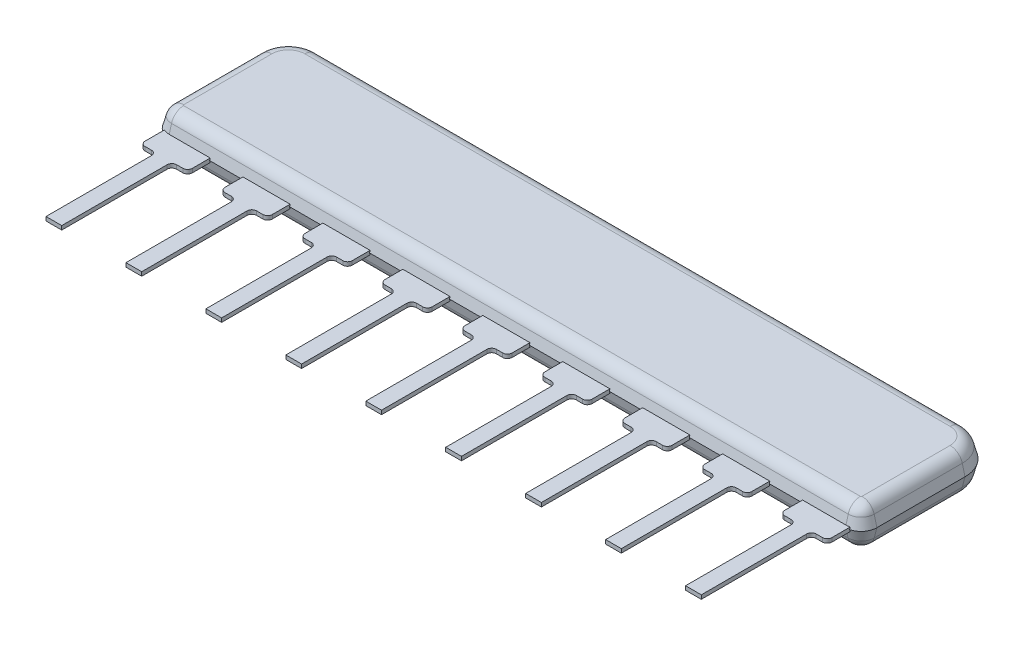
SolidWorks part; units mm, degrees
ref_plane "Front" through (0, 0, 0) normal (0, 0, 1) x (1, 0, 0)
ref_plane "Top" through (0, 0, 0) normal (0, 1, 0) x (1, 0, 0)
ref_plane "Right" through (0, 0, 0) normal (1, 0, 0) x (0, 0, -1)
sketch "Sketch1" plane through (0, 0, 0) normal (0, 1, 0) x (1, 0, 0)
  line L1 (0.5, 0) -> (22, 0)
  line L2 (0, 0.5) -> (0, 3.3)
  line L3 (1, 4.3) -> (21.5, 4.3)
  line L4 (22.5, 0.5) -> (22.5, 3.3)
  arc A0 (0, 3.3) -> (1, 4.3) centre (1, 3.3) cw
  arc A2 (22.5, 3.3) -> (21.5, 4.3) centre (21.5, 3.3) ccw
  arc A4 (0.5, 0) -> (0, 0.5) centre (0.5, 0.5) cw
  arc A5 (22, 0) -> (22.5, 0.5) centre (22, 0.5) ccw
  point P7 (0, 4.3)
  point P10 (0, 0)
  point P13 (22.5, 4.3)
  point P16 (22.5, 0)
  dimension "D3" = 1
  dimension "D4" = 0.5
  dimension "D1" = 22.5
  dimension "D2" = 4.3
extrude "Extrude1" add sketch "Sketch1" along normal mid plane 1.25 draft 15
sketch "Sketch2" plane through (0, 0, 0) normal (0, 1, 0) x (1, 0, 0)
  line L0 (0.3, 0.4022) -> (0.3, -0.55)
  line L2 (0.45, -0.7) -> (0.65, -0.7)
  line L3 (0.8, -0.85) -> (0.8, -4.2)
  line L4 (0.8, -4.2) -> (1.3, -4.2)
  line L5 (1.3, -4.2) -> (1.3, -0.85)
  line L6 (1.45, -0.7) -> (1.65, -0.7)
  line L7 (1.8, -0.55) -> (1.8, 0.4022)
  line L8 (0.3, 0.4022) -> (1.8, 0.4022)
  line L9 (2.84, 0.4022) -> (2.84, -0.55)
  line L10 (2.99, -0.7) -> (3.19, -0.7)
  line L11 (3.34, -0.85) -> (3.34, -4.2)
  line L12 (3.34, -4.2) -> (3.84, -4.2)
  line L13 (3.84, -4.2) -> (3.84, -0.85)
  line L14 (3.99, -0.7) -> (4.19, -0.7)
  line L15 (4.34, -0.55) -> (4.34, 0.4022)
  line L16 (2.84, 0.4022) -> (4.34, 0.4022)
  line L17 (5.38, 0.4022) -> (5.38, -0.55)
  line L18 (5.53, -0.7) -> (5.73, -0.7)
  line L19 (5.88, -0.85) -> (5.88, -4.2)
  line L20 (5.88, -4.2) -> (6.38, -4.2)
  line L21 (6.38, -4.2) -> (6.38, -0.85)
  line L22 (6.53, -0.7) -> (6.73, -0.7)
  line L23 (6.88, -0.55) -> (6.88, 0.4022)
  line L24 (5.38, 0.4022) -> (6.88, 0.4022)
  line L25 (7.92, 0.4022) -> (7.92, -0.55)
  line L26 (8.07, -0.7) -> (8.27, -0.7)
  line L27 (8.42, -0.85) -> (8.42, -4.2)
  line L28 (8.42, -4.2) -> (8.92, -4.2)
  line L29 (8.92, -4.2) -> (8.92, -0.85)
  line L30 (9.07, -0.7) -> (9.27, -0.7)
  line L31 (9.42, -0.55) -> (9.42, 0.4022)
  line L32 (7.92, 0.4022) -> (9.42, 0.4022)
  line L33 (10.46, 0.4022) -> (10.46, -0.55)
  line L34 (10.61, -0.7) -> (10.81, -0.7)
  line L35 (10.96, -0.85) -> (10.96, -4.2)
  line L36 (10.96, -4.2) -> (11.46, -4.2)
  line L37 (11.46, -4.2) -> (11.46, -0.85)
  line L38 (11.61, -0.7) -> (11.81, -0.7)
  line L39 (11.96, -0.55) -> (11.96, 0.4022)
  line L40 (10.46, 0.4022) -> (11.96, 0.4022)
  line L41 (13, 0.4022) -> (13, -0.55)
  line L42 (13.15, -0.7) -> (13.35, -0.7)
  line L43 (13.5, -0.85) -> (13.5, -4.2)
  line L44 (13.5, -4.2) -> (14, -4.2)
  line L45 (14, -4.2) -> (14, -0.85)
  line L46 (14.15, -0.7) -> (14.35, -0.7)
  line L47 (14.5, -0.55) -> (14.5, 0.4022)
  line L48 (13, 0.4022) -> (14.5, 0.4022)
  line L49 (15.54, 0.4022) -> (15.54, -0.55)
  line L50 (15.69, -0.7) -> (15.89, -0.7)
  line L51 (16.04, -0.85) -> (16.04, -4.2)
  line L52 (16.04, -4.2) -> (16.54, -4.2)
  line L53 (16.54, -4.2) -> (16.54, -0.85)
  line L54 (16.69, -0.7) -> (16.89, -0.7)
  line L55 (17.04, -0.55) -> (17.04, 0.4022)
  line L56 (15.54, 0.4022) -> (17.04, 0.4022)
  line L57 (18.08, 0.4022) -> (18.08, -0.55)
  line L58 (18.23, -0.7) -> (18.43, -0.7)
  line L59 (18.58, -0.85) -> (18.58, -4.2)
  line L60 (18.58, -4.2) -> (19.08, -4.2)
  line L61 (19.08, -4.2) -> (19.08, -0.85)
  line L62 (19.23, -0.7) -> (19.43, -0.7)
  line L63 (19.58, -0.55) -> (19.58, 0.4022)
  line L64 (18.08, 0.4022) -> (19.58, 0.4022)
  line L65 (20.62, 0.4022) -> (20.62, -0.55)
  line L66 (20.77, -0.7) -> (20.97, -0.7)
  line L67 (21.12, -0.85) -> (21.12, -4.2)
  line L68 (21.12, -4.2) -> (21.62, -4.2)
  line L69 (21.62, -4.2) -> (21.62, -0.85)
  line L70 (21.77, -0.7) -> (21.97, -0.7)
  line L71 (22.12, -0.55) -> (22.12, 0.4022)
  line L72 (20.62, 0.4022) -> (22.12, 0.4022)
  line L73 (0, 3.3) -> (0, 0.5) construction
  line L75 (0.5, 0) -> (22, 0) construction
  arc A0 (0.3, -0.55) -> (0.45, -0.7) centre (0.45, -0.55) ccw
  arc A1 (1.8, -0.55) -> (1.65, -0.7) centre (1.65, -0.55) cw
  arc A2 (1.3, -0.85) -> (1.45, -0.7) centre (1.45, -0.85) cw
  arc A3 (0.65, -0.7) -> (0.8, -0.85) centre (0.65, -0.85) cw
  arc A4 (2.84, -0.55) -> (2.99, -0.7) centre (2.99, -0.55) ccw
  arc A5 (4.34, -0.55) -> (4.19, -0.7) centre (4.19, -0.55) cw
  arc A6 (3.84, -0.85) -> (3.99, -0.7) centre (3.99, -0.85) cw
  arc A7 (3.19, -0.7) -> (3.34, -0.85) centre (3.19, -0.85) cw
  arc A8 (5.38, -0.55) -> (5.53, -0.7) centre (5.53, -0.55) ccw
  arc A9 (6.88, -0.55) -> (6.73, -0.7) centre (6.73, -0.55) cw
  arc A10 (6.38, -0.85) -> (6.53, -0.7) centre (6.53, -0.85) cw
  arc A11 (5.73, -0.7) -> (5.88, -0.85) centre (5.73, -0.85) cw
  arc A12 (7.92, -0.55) -> (8.07, -0.7) centre (8.07, -0.55) ccw
  arc A13 (9.42, -0.55) -> (9.27, -0.7) centre (9.27, -0.55) cw
  arc A14 (8.92, -0.85) -> (9.07, -0.7) centre (9.07, -0.85) cw
  arc A15 (8.27, -0.7) -> (8.42, -0.85) centre (8.27, -0.85) cw
  arc A16 (10.46, -0.55) -> (10.61, -0.7) centre (10.61, -0.55) ccw
  arc A17 (11.96, -0.55) -> (11.81, -0.7) centre (11.81, -0.55) cw
  arc A18 (11.46, -0.85) -> (11.61, -0.7) centre (11.61, -0.85) cw
  arc A19 (10.81, -0.7) -> (10.96, -0.85) centre (10.81, -0.85) cw
  arc A20 (13, -0.55) -> (13.15, -0.7) centre (13.15, -0.55) ccw
  arc A21 (14.5, -0.55) -> (14.35, -0.7) centre (14.35, -0.55) cw
  arc A22 (14, -0.85) -> (14.15, -0.7) centre (14.15, -0.85) cw
  arc A23 (13.35, -0.7) -> (13.5, -0.85) centre (13.35, -0.85) cw
  arc A24 (15.54, -0.55) -> (15.69, -0.7) centre (15.69, -0.55) ccw
  arc A25 (17.04, -0.55) -> (16.89, -0.7) centre (16.89, -0.55) cw
  arc A26 (16.54, -0.85) -> (16.69, -0.7) centre (16.69, -0.85) cw
  arc A27 (15.89, -0.7) -> (16.04, -0.85) centre (15.89, -0.85) cw
  arc A28 (18.08, -0.55) -> (18.23, -0.7) centre (18.23, -0.55) ccw
  arc A29 (19.58, -0.55) -> (19.43, -0.7) centre (19.43, -0.55) cw
  arc A30 (19.08, -0.85) -> (19.23, -0.7) centre (19.23, -0.85) cw
  arc A31 (18.43, -0.7) -> (18.58, -0.85) centre (18.43, -0.85) cw
  arc A32 (20.62, -0.55) -> (20.77, -0.7) centre (20.77, -0.55) ccw
  arc A33 (22.12, -0.55) -> (21.97, -0.7) centre (21.97, -0.55) cw
  arc A34 (21.62, -0.85) -> (21.77, -0.7) centre (21.77, -0.85) cw
  arc A35 (20.97, -0.7) -> (21.12, -0.85) centre (20.97, -0.85) cw
  point P12 (0.3, -0.7)
  dimension "D5" = 0.15
  dimension "D1" = 0.7
  dimension "D2" = 1.5
  dimension "D3" = 0.5
  dimension "D4" = 0.5
  dimension "D6" = 0.3
  dimension "D7" = 3.5
extrude "Extrude2" add sketch "Sketch2" along normal mid plane 0.125
fillet "Fillet1" radius 0.4 16 edges at (0.2649, -0.625, -0.2649) (11.25, -0.625, -0.1675) (22.2351, -0.625, -0.2649) (22.3325, -0.625, -1.9) (22.0887, -0.625, -3.8887) (11.25, -0.625, -4.1325) (0.4113, 0.625, -3.8887) (0.1675, 0.625, -1.9) (0.2649, 0.625, -0.2649) (11.25, 0.625, -0.1675) (22.2351, 0.625, -0.2649) (22.3325, 0.625, -1.9) (22.0887, 0.625, -3.8887) (11.25, 0.625, -4.1325) (0.4113, -0.625, -3.8887) (0.1675, -0.625, -1.9)
